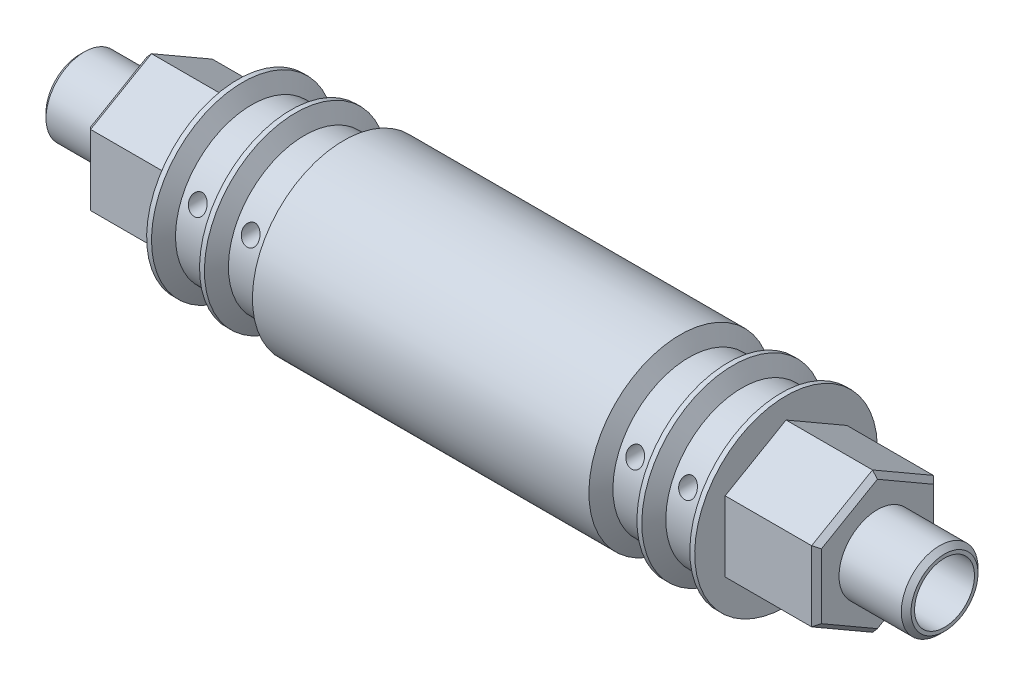
SolidWorks part; units mm, degrees
ref_plane "Front Plane" through (0, 0, 0) normal (0, 0, 1) x (1, 0, 0)
ref_plane "Top Plane" through (0, 0, 0) normal (0, 1, 0) x (1, 0, 0)
ref_plane "Right Plane" through (0, 0, 0) normal (1, 0, 0) x (0, 0, -1)
sketch "Sketch1" plane through (0, 0, 0) normal (0, 0, 1) x (1, 0, 0)
  line L0 (-38.1, 0) -> (38.1, 0) construction
  line L1 (-28.067, 9.525) -> (-27.1505, 7.9375)
  line L2 (-27.1505, 7.9375) -> (-23.9755, 7.9375)
  line L3 (-23.9755, 7.9375) -> (-23.0589, 9.525)
  line L4 (-23.0589, 9.525) -> (-22.5509, 9.525)
  line L5 (-22.5509, 9.525) -> (-21.6344, 7.9375)
  line L6 (-21.6344, 7.9375) -> (-18.4594, 7.9375)
  line L7 (-18.4594, 7.9375) -> (-17.5428, 9.525)
  line L8 (0, 0) -> (0, 25.6809) construction
  line L9 (-17.5428, 9.525) -> (0, 9.525)
  line L10 (-22.8049, 9.525) -> (-22.8049, 0) construction
  line L11 (-28.575, 9.525) -> (-28.575, 4.254)
  line L12 (-28.575, 4.254) -> (-38.1, 4.254)
  line L13 (-38.1, 4.254) -> (-38.1, 4)
  line L14 (-38.1, 0) -> (-28.575, 0)
  line L15 (-28.575, 0) -> (0, 0)
  line L16 (-28.067, 9.525) -> (-28.575, 9.525)
  line L17 (0, 0) -> (0, 9.525)
  line L18 (-38.1, 0) -> (-38.1, -4) construction
  line L19 (-28.575, 4.254) -> (-28.575, 0) construction
  line L20 (-45.1, 4) -> (-45.1, 0)
  line L21 (-45.1, 4) -> (-38.1, 4)
  line L22 (-45.1, 0) -> (-45.1, -4) construction
  line L23 (-38.1, 4) -> (-38.1, 0) construction
  line L24 (-38.1, 0) -> (-45.1, 0)
  line L25 (-45.1, 1.6) -> (-35.275, 1.6)
  line L26 (-35.275, 1.6) -> (-33.675, 0)
  line L27 (-45.1, 1.6) -> (-45.1, -1.6) construction
  line L28 (-48.275, -1.5) -> (-35.275, -1.5) construction
  line L29 (-48.275, -1.5) -> (-48.275, 1.5) construction
  line L30 (-48.275, 1.5) -> (-35.275, 1.5) construction
  line L31 (-35.275, -1.5) -> (-35.275, 1.5) construction
  line L32 (-48.275, -1.5) -> (-35.275, 1.5) construction
  line L33 (-48.275, 1.5) -> (-35.275, -1.5) construction
  point P27 (-41.775, 0)
  point P40 (-45.1, 0)
  dimension "D2" = 3.175
  dimension "D3" = 1.5875
  dimension "D4" = 60
  dimension "D6" = 1.5875
  dimension "D5" = 0.508
  dimension "D7" = 1.5875
  dimension "D8" = 0.508
  dimension "D11" = 9.525
  dimension "D12" = 8
  dimension "D13" = 7
  dimension "D10" = 0.254
  dimension "D9" = 76.2
  dimension "D14" = 9.525
  dimension "D15" = 13
  dimension "D16" = 3
  dimension "D17" = 3.175
  dimension "D18" = 45
  dimension "D19" = 3.2
revolve "Revolve1" add sketch "Sketch1" angle 360 about L0
sketch "Sketch4" plane through (-28.575, 0, 0) normal (-1, 0, 0) x (0, 0, 1)
  line L1 (0, 7.3323) -> (-6.35, 3.6662)
  line L2 (-6.35, 3.6662) -> (-6.35, -3.6662)
  line L3 (-6.35, -3.6662) -> (0, -7.3323)
  line L4 (0, -7.3323) -> (6.35, -3.6662)
  line L5 (6.35, -3.6662) -> (6.35, 3.6662)
  line L6 (6.35, 3.6662) -> (0, 7.3323)
  circle A0 centre (0, 0) radius 6.35 construction
  dimension "D1" = 12.7
extrude "Boss-Extrude4" add sketch "Sketch4" along normal up to surface (9.525 mm away) up to face at (-38.1, -4, 0)
sketch "Sketch6" plane through (0, 0, 0) normal (0, 0, 1) x (1, 0, 0)
  line L0 (-25.563, 7.9375) -> (-25.563, 3.302) construction
  line L1 (-27.1505, 7.9375) -> (-23.9755, 7.9375) construction
  line L2 (-20.0469, 7.9375) -> (-20.0469, 3.302) construction
  line L3 (-21.6344, 7.9375) -> (-18.4594, 7.9375) construction
  circle A0 centre (-25.563, 3.302) radius 0.889
  circle A1 centre (-20.0469, 3.302) radius 0.889
  dimension "D1" = 1.778
  dimension "D2" = 3.302
extrude "Cut-Extrude1" cut sketch "Sketch6" against normal through all both and the other way through all
chamfer "Chamfer2" distance 0.508 angle 45 6 edges at (-38.1, 0, 6.35) (-38.1, -5.4993, 3.175) (-38.1, -5.4993, -3.175) (-38.1, 0, -6.35) (-38.1, 5.4993, -3.175) (-38.1, 5.4993, 3.175)
chamfer "Chamfer3" distance 0.508 angle 45 1 edges at (-45.1, -4, 0)
mirror "Mirror2" about plane through (0, 0, 0) normal (1, 0, 0) of bodies 107
sketch "Sketch7" plane through (-45.1, 0, 0) normal (-1, 0, 0) x (0, 0, 1)
  circle A0 centre (0, 0) radius 3.125
  dimension "D1" = 6.25
extrude "Cut-Extrude2" cut sketch "Sketch7" against normal through all
equation "\"D12@Sketch1\"=8mm"
equation "\"D19@Sketch1\"=3.2mm"
equation "\"D1@Sketch7\"=6mm+.25mm"
